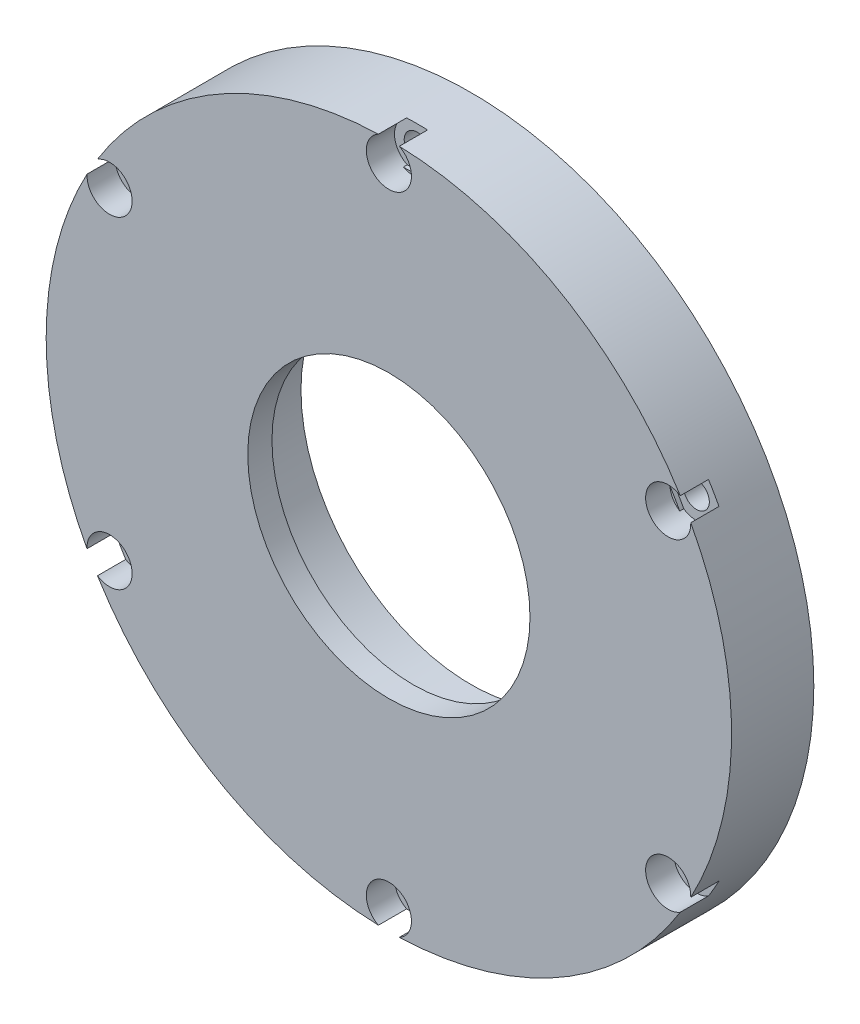
SolidWorks part; units mm, degrees
ref_plane "Front Plane" through (0, 0, 0) normal (0, 0, 1) x (1, 0, 0)
ref_plane "Top Plane" through (0, 0, 0) normal (0, 1, 0) x (1, 0, 0)
ref_plane "Right Plane" through (0, 0, 0) normal (1, 0, 0) x (0, 0, -1)
sketch "Sketch1" plane through (0, 0, 0) normal (0, 0, 1) x (1, 0, 0)
  circle A2 centre (-319.7082, 27.5786) radius 42.5
  circle A6 centre (-285.0672, 47.5786) radius 1.6
  circle A7 centre (-285.0672, 7.5786) radius 1.6
  circle A8 centre (-319.7082, -12.4214) radius 1.6
  circle A9 centre (-354.3493, 7.5786) radius 1.6
  circle A10 centre (-354.3493, 47.5786) radius 1.6
  circle A11 centre (-319.7082, 67.5786) radius 1.6
  circle A12 centre (-319.7082, 27.5786) radius 17.5
  point P19 (-319.7082, 27.5786)
  dimension "D2" = 6
extrude "Boss-Extrude1" add sketch "Sketch1" along normal blind 3
sketch "Sketch2" plane through (0, 0, 0) normal (0, 0, -1) x (-1, 0, 0)
  circle A0 centre (319.7082, 27.5786) radius 37.5
  circle A1 centre (319.7082, 27.5786) radius 21.1
  circle A3 centre (354.3493, 7.5786) radius 1.6
  circle A4 centre (354.3493, 7.5786) radius 1.6
  circle A5 centre (319.7082, -12.4214) radius 1.6
  circle A6 centre (319.7082, -12.4214) radius 1.6
  circle A7 centre (285.0672, 7.5786) radius 1.6
  circle A8 centre (285.0672, 7.5786) radius 1.6
  circle A9 centre (285.0672, 47.5786) radius 1.6
  circle A10 centre (285.0672, 47.5786) radius 1.6
  circle A11 centre (319.7082, 27.5786) radius 42.5
  circle A12 centre (319.7082, 27.5786) radius 42.5
  circle A13 centre (319.7082, 67.5786) radius 1.6
  circle A14 centre (319.7082, 67.5786) radius 1.6
  circle A15 centre (354.3493, 47.5786) radius 1.6
  circle A16 centre (354.3493, 47.5786) radius 1.6
  circle A17 centre (319.7082, 27.5786) radius 24.1
  circle M9 centre (319.7082, 27.5786) radius 42.5
  circle M10 centre (285.0672, 47.5786) radius 1.6
  circle M12 centre (285.0672, 7.5786) radius 1.6
  circle M13 centre (319.7082, -12.4214) radius 1.6
  circle M14 centre (354.3493, 7.5786) radius 1.6
  circle M15 centre (354.3493, 47.5786) radius 1.6
  circle M16 centre (319.7082, 67.5786) radius 1.6
  dimension "D9" = 3
  dimension "D1" = 5
  dimension "D2" = 0
  dimension "D3" = 0
  dimension "D4" = 0
  dimension "D5" = 0
  dimension "D6" = 0
  dimension "D7" = 0
  dimension "D8" = 0
extrude "Boss-Extrude3" add sketch "Sketch2" along normal blind 7.2 contours A17 A1 | A0 M9 M10 M12 M14 M16 M15 M13
sketch "Sketch3" plane through (0, 0, 3) normal (0, 0, 1) x (1, 0, 0)
  circle A0 centre (-285.0672, 47.5786) radius 2.8
  circle A1 centre (-285.0672, 7.5786) radius 2.8
  circle A2 centre (-319.7082, -12.4214) radius 2.8
  circle A3 centre (-354.3493, 7.5786) radius 2.8
  circle A4 centre (-354.3493, 47.5786) radius 2.8
  circle A5 centre (-319.7082, 67.5786) radius 2.8
  point P4 (-319.7082, 27.5786)
  point P18 (-319.7082, 27.5786)
  dimension "D1" = 6
extrude "Cut-Extrude1" cut sketch "Sketch3" against normal blind 3.5
sketch "Sketch4" plane through (0, 0, -7.2) normal (0, 0, -1) x (-1, 0, 0)
  circle A2 centre (319.7082, 27.5786) radius 37.5
  circle A3 centre (319.7082, 27.5786) radius 24.1 construction
  circle A4 centre (319.7082, 27.5786) radius 24.1
extrude "Boss-Extrude4" add sketch "Sketch4" against normal up to surface (7.2 mm away) up to face at (-302.2082, 27.5786, 0)
sketch "Sketch23" plane through (0, 0, -7.2) normal (0, 0, -1) x (-1, 0, 0)
  circle A0 centre (319.7082, 27.5786) radius 42.5 construction
  circle A1 centre (319.7082, 27.5786) radius 42.5
  circle A2 centre (319.7082, 27.5786) radius 37.5
  circle A5 centre (319.7082, 27.5786) radius 24.1
  dimension "D1" = 5
extrude "Cut-Extrude3" cut sketch "Sketch23" against normal blind 3 contours A2 A5
fillet "Fillet1" radius 1.5 2 edges at (-357.2082, 27.5786, -4.2) (-343.8082, 27.5786, -4.2)
